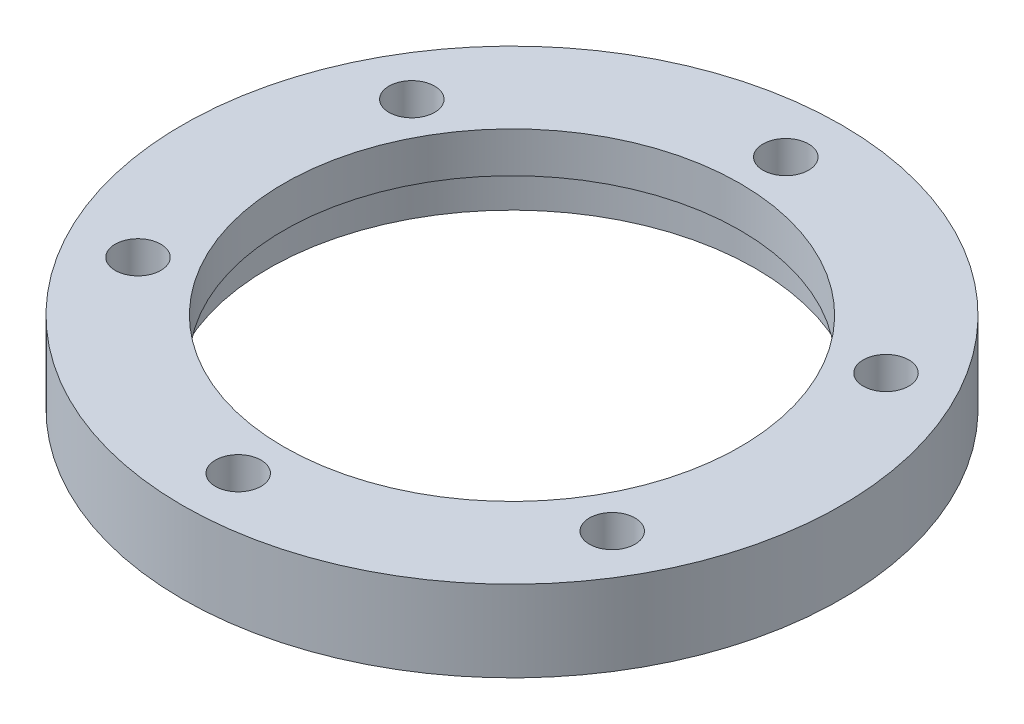
SolidWorks part; units mm, degrees
material "6061-T6 (SS)"
ref_plane "Front Plane" through (0, 0, 0) normal (0, 0, 1) x (1, 0, 0)
ref_plane "Top Plane" through (0, 0, 0) normal (0, 1, 0) x (1, 0, 0)
ref_plane "Right Plane" through (0, 0, 0) normal (1, 0, 0) x (0, 0, -1)
sketch "Sketch1" plane through (0, 0, 0) normal (0, 0, 1) x (1, 0, 0)
  line L0 (0, 0) -> (0, 34.1875) construction
  line L1 (-32.5, 0) -> (-32.5, 8)
  line L2 (-32.5, 8) -> (-22.5, 8)
  line L3 (-22.5, 8) -> (-22.5, 4)
  line L4 (-22.5, 4) -> (-24, 4)
  line L5 (-24, 4) -> (-24, 0)
  line L6 (-24, 0) -> (-32.5, 0)
  dimension "D1" = 48
  dimension "D2" = 45
  dimension "D3" = 4
  dimension "D4" = 8
  dimension "D5" = 65
revolve "Revolve1" add sketch "Sketch1" angle 360 about L0
sketch "Sketch2" plane through (0, 8, 0) normal (0, 1, 0) x (1, 0, 0)
  circle A0 centre (0, 0) radius 27 construction
  circle A1 centre (0, 27) radius 2.25
  circle A2 centre (23.3827, 13.5) radius 2.25
  circle A3 centre (23.3827, -13.5) radius 2.25
  circle A4 centre (0, -27) radius 2.25
  circle A5 centre (-23.3827, -13.5) radius 2.25
  circle A6 centre (-23.3827, 13.5) radius 2.25
  point P17 (0, 0)
  dimension "D1" = 54
  dimension "D2" = 4.5
  dimension "D3" = 6
extrude "Cut-Extrude1" cut sketch "Sketch2" against normal blind 10
